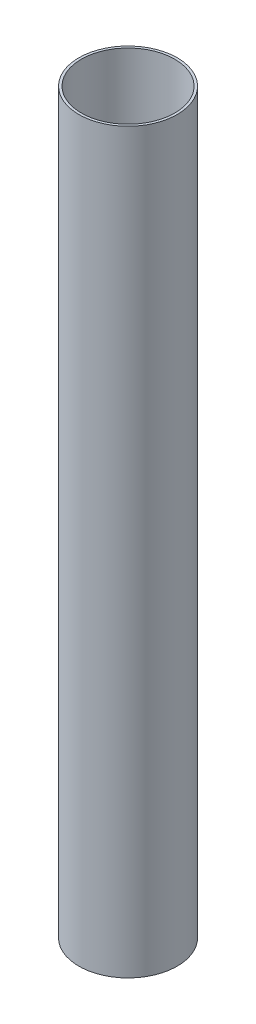
SolidWorks part; units mm, degrees
ref_plane "Front Plane" through (0, 0, 0) normal (0, 0, 1) x (1, 0, 0)
ref_plane "Top Plane" through (0, 0, 0) normal (0, 1, 0) x (1, 0, 0)
ref_plane "Right Plane" through (0, 0, 0) normal (1, 0, 0) x (0, 0, -1)
sketch "Sketch1" plane through (0, 0, 0) normal (0, 1, 0) x (1, 0, 0)
  circle A0 centre (0, 0) radius 20.32
  circle A1 centre (0, 0) radius 19.304
  dimension "D1" = 38.608
  dimension "D2" = 40.64
extrude "Boss-Extrude1" add sketch "Sketch1" along normal mid plane 304.8
